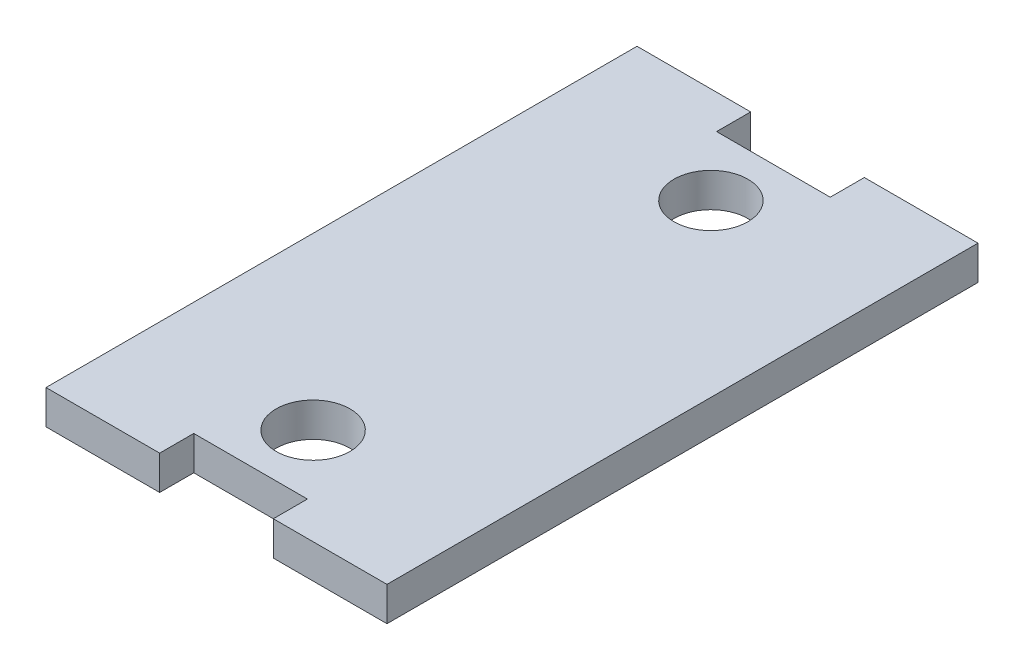
SolidWorks part; units mm, degrees
ref_plane "Front" through (0, 0, 0) normal (0, 0, 1) x (1, 0, 0)
ref_plane "Top" through (0, 0, 0) normal (0, 1, 0) x (1, 0, 0)
ref_plane "Right" through (0, 0, 0) normal (1, 0, 0) x (0, 0, -1)
sketch "Sketch1" plane through (0, 0, 0) normal (0, 1, 0) x (1, 0, 0)
  line L0 (-11.4489, 0) -> (16.6876, 0) construction
  line L1 (-7.5, 13) -> (-2.5, 13)
  line L2 (-7.5, 13) -> (-7.5, -13)
  line L3 (-7.5, -13) -> (-2.5, -13)
  line L4 (7.5, 13) -> (7.5, -13)
  line L5 (-7.5, 13) -> (7.5, -13) construction
  line L6 (-7.5, -13) -> (7.5, 13) construction
  line L7 (2.5, 11.5) -> (-2.5, 11.5)
  line L8 (2.5, 11.5) -> (2.5, 13)
  line L10 (-2.5, 11.5) -> (-2.5, 13)
  line L11 (2.5, 11.5) -> (-2.5, 13) construction
  line L12 (2.5, 13) -> (-2.5, 11.5) construction
  line L13 (2.5, -13) -> (-2.5, -11.5) construction
  line L14 (2.5, -11.5) -> (-2.5, -13) construction
  line L15 (-2.5, -11.5) -> (-2.5, -13)
  line L17 (2.5, -11.5) -> (2.5, -13)
  line L18 (2.5, -11.5) -> (-2.5, -11.5)
  line L19 (2.5, -13) -> (7.5, -13)
  line L20 (2.5, 13) -> (7.5, 13)
  circle A0 centre (0, 8.75) radius 1.625
  circle A1 centre (0, -8.75) radius 1.625
  point P0 (0, 0)
  point P6 (0, 12.25)
  point P17 (0, -12.25)
  point P20 (0, 0)
  dimension "D5" = 3.25
  dimension "D1" = 15
  dimension "D2" = 26
  dimension "D3" = 5
  dimension "D4" = 1.5
  dimension "D6" = 17.5
extrude "Boss-Extrude1" add sketch "Sketch1" along normal blind 1.5
